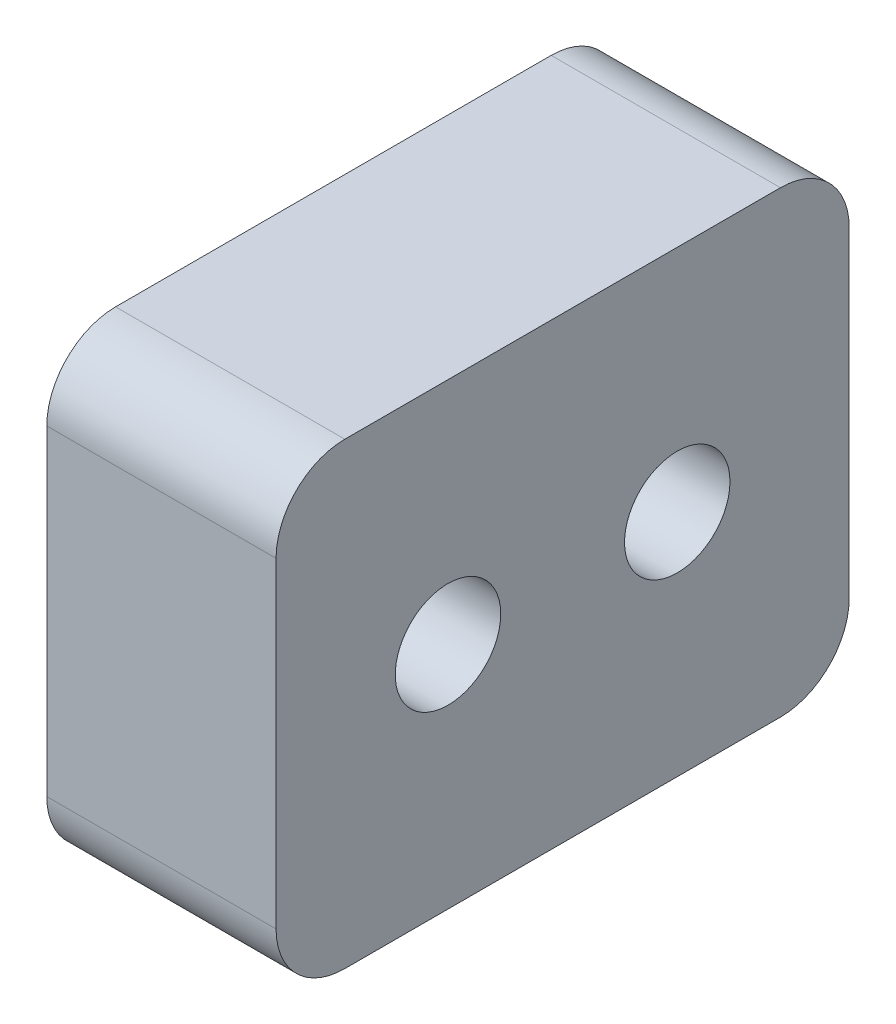
SolidWorks part; units mm, degrees
ref_plane "前视基准面" through (0, 0, 0) normal (0, 0, 1) x (1, 0, 0)
ref_plane "上视基准面" through (0, 0, 0) normal (0, 1, 0) x (1, 0, 0)
ref_plane "右视基准面" through (0, 0, 0) normal (1, 0, 0) x (0, 0, -1)
other "Configuration Table"
sketch "草图1" plane through (0, 0, 0) normal (1, 0, 0) x (0, 0, -1)
  line L1 (0, 0) -> (25, 0)
  line L2 (0, 0) -> (0, 20)
  line L3 (0, 20) -> (25, 20)
  line L4 (25, 0) -> (25, 20)
  circle A0 centre (7.5, 10) radius 2.3
  circle A1 centre (17.5, 10) radius 2.3
  dimension "D3" = 4.6
  dimension "D4" = 4.6
  dimension "D5" = 7.5
  dimension "D6" = 10
  dimension "D7" = 10
  dimension "D1" = 25
  dimension "D2" = 20
extrude "凸台-拉伸1" add sketch "草图1" along normal blind 10
fillet "圆角1" radius 3 4 edges at (5, 0, 0) (5, 20, 0) (5, 0, -25) (5, 20, -25)
